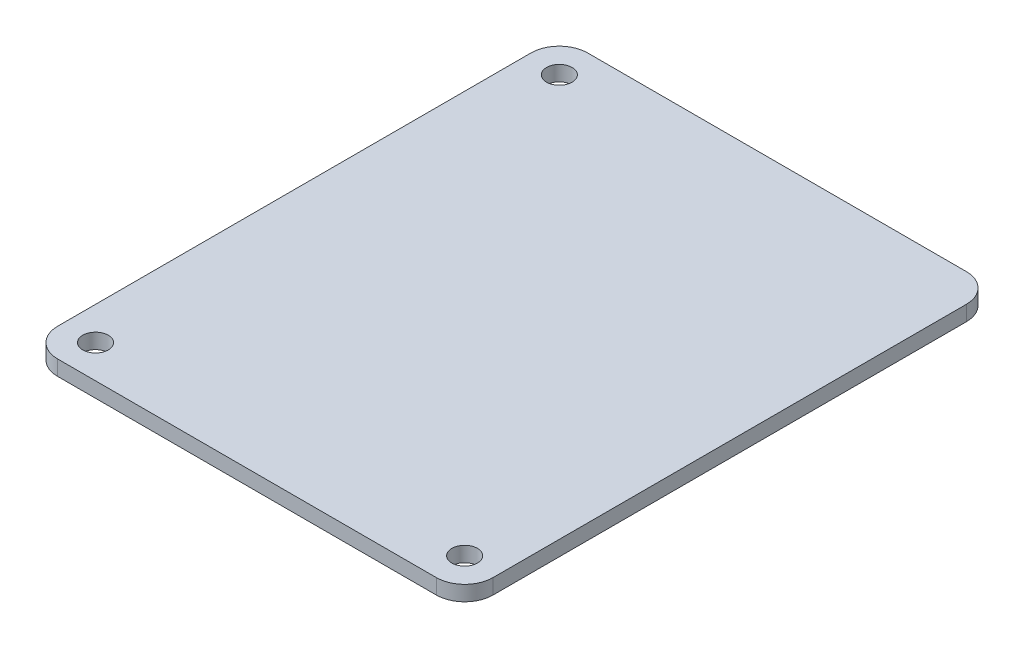
SolidWorks part; units mm, degrees
ref_plane "Ön Düzlem" through (0, 0, 0) normal (0, 0, 1) x (1, 0, 0)
ref_plane "Üst Düzlem" through (0, 0, 0) normal (0, 1, 0) x (1, 0, 0)
ref_plane "Sağ Düzlem" through (0, 0, 0) normal (1, 0, 0) x (0, 0, -1)
sketch "Çizim1" plane through (0, 0, 0) normal (0, 1, 0) x (1, 0, 0)
  line L1 (-20, -28) -> (20, -28)
  line L2 (-23, -25) -> (-23, 25)
  line L3 (-20, 28) -> (20, 28)
  line L4 (23, -25) -> (23, 25)
  line L5 (-23, -28) -> (23, 28) construction
  line L6 (-23, 28) -> (23, -28) construction
  arc A0 (-20, -28) -> (-23, -25) centre (-20, -25) cw
  arc A1 (-23, 25) -> (-20, 28) centre (-20, 25) cw
  arc A2 (20, 28) -> (23, 25) centre (20, 25) cw
  arc A3 (20, -28) -> (23, -25) centre (20, -25) ccw
  point P0 (0, 0)
  dimension "D3" = 3
  dimension "D1" = 56
  dimension "D2" = 46
extrude "Yükseklik-Ekstrüzyon1" add sketch "Çizim1" along normal blind 1.6
sketch "Çizim2" plane through (0, 1.6, 0) normal (0, 1, 0) x (1, 0, 0)
  line L0 (0, 36.4052) -> (0, -40.2958) construction
  line L1 (-35.4603, 0) -> (38.3505, 0) construction
  line L2 (20, 28) -> (-20, 28) construction
  line L4 (-23, 25) -> (-23, -25) construction
  circle A0 centre (-19.5, 24.5) radius 1.35
  circle A2 centre (19.5, -24.5) radius 1.35
  circle A4 centre (-19.5, -24.5) radius 1.35
  dimension "D1" = 2.7
  dimension "D2" = 3.5
  dimension "D3" = 3.5
extrude "Kes-Ekstrüzyon1" cut sketch "Çizim2" against normal blind 1.6
